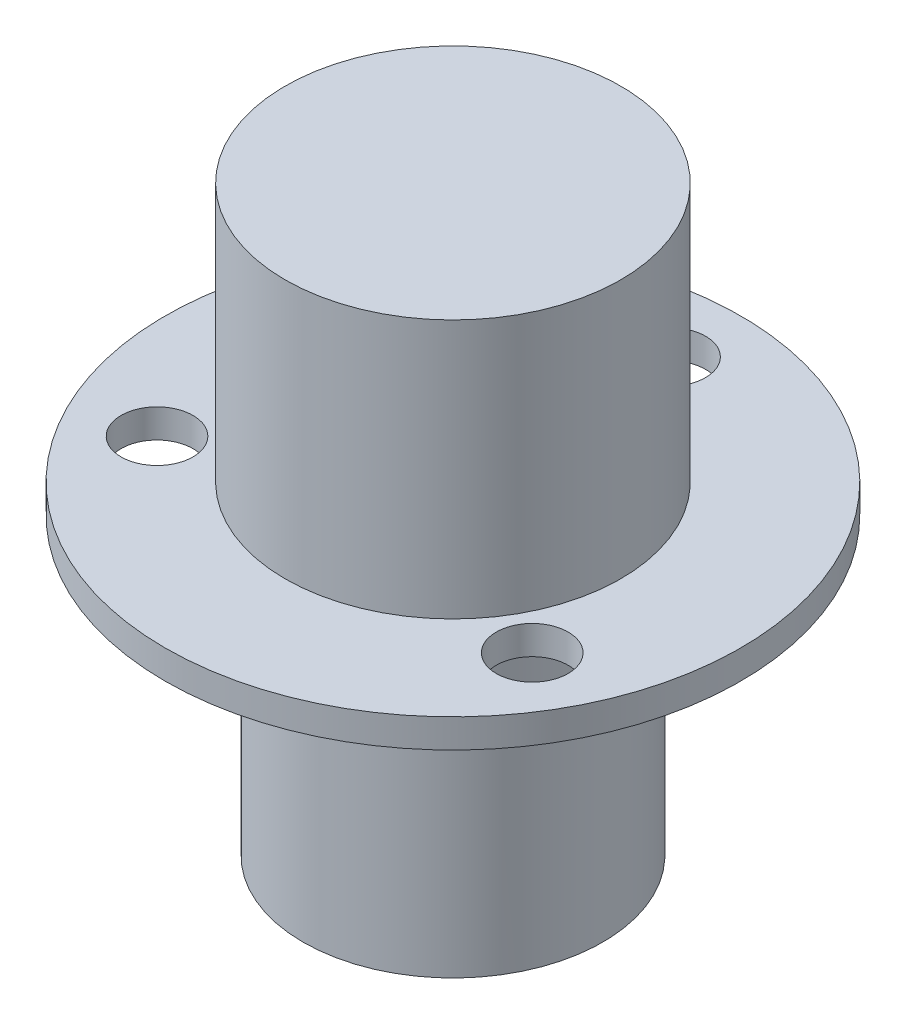
SolidWorks part; units mm, degrees
ref_plane "Front Plane" through (0, 0, 0) normal (0, 0, 1) x (1, 0, 0)
ref_plane "Top Plane" through (0, 0, 0) normal (0, 1, 0) x (1, 0, 0)
ref_plane "Right Plane" through (0, 0, 0) normal (1, 0, 0) x (0, 0, -1)
sketch "Sketch1" plane through (0, 0, 0) normal (0, 1, 0) x (1, 0, 0)
  circle A0 centre (0, 0) radius 12
  circle A1 centre (0, 0) radius 2.5
  dimension "D1" = 24
  dimension "D2" = 5
extrude "Boss-Extrude1" add sketch "Sketch1" along normal blind 1.2
sketch "Sketch2" plane through (0, 1.2, 0) normal (0, 1, 0) x (1, 0, 0)
  line L0 (0, 9.0345) -> (0, 0)
  line L1 (0, 0) -> (7.8241, -4.5172)
  line L2 (7.8241, -4.5172) -> (0, 0)
  line L3 (0, 0) -> (-7.8241, -4.5172)
  circle A0 centre (0, 0) radius 9.0345
  circle A1 centre (0, 9.0345) radius 1.5
  circle A2 centre (7.8241, -4.5172) radius 1.5
  circle A3 centre (-7.8241, -4.5172) radius 1.5
  dimension "D3" = 3
  dimension "D4" = 3
  dimension "D5" = 3
  dimension "D6" = 18.0689
  dimension "D1" = 120
  dimension "D2" = 120
extrude "Cut-Extrude1" cut sketch "Sketch2" against normal blind 1.2 contours A0 A1 L0 | L0 A1 A0 | A0 A1 | A0 A2 | A0 A2 L2 | L2 A2 A0 | A0 A3 L3 | L3 A3 A0 | A0 A3
sketch "Sketch3" plane through (0, 0, 0) normal (0, -1, 0) x (-1, 0, 0)
  circle A0 centre (0, 0) radius 6.25
  dimension "D1" = 12.5
extrude "Boss-Extrude2" add sketch "Sketch3" along normal blind 12.3
sketch "Sketch4" plane through (0, 0, 0) normal (0, 1, 0) x (1, 0, 0)
  circle A0 centre (0, 0) radius 7
  dimension "D1" = 14
extrude "Boss-Extrude3" add sketch "Sketch4" along normal blind 12
